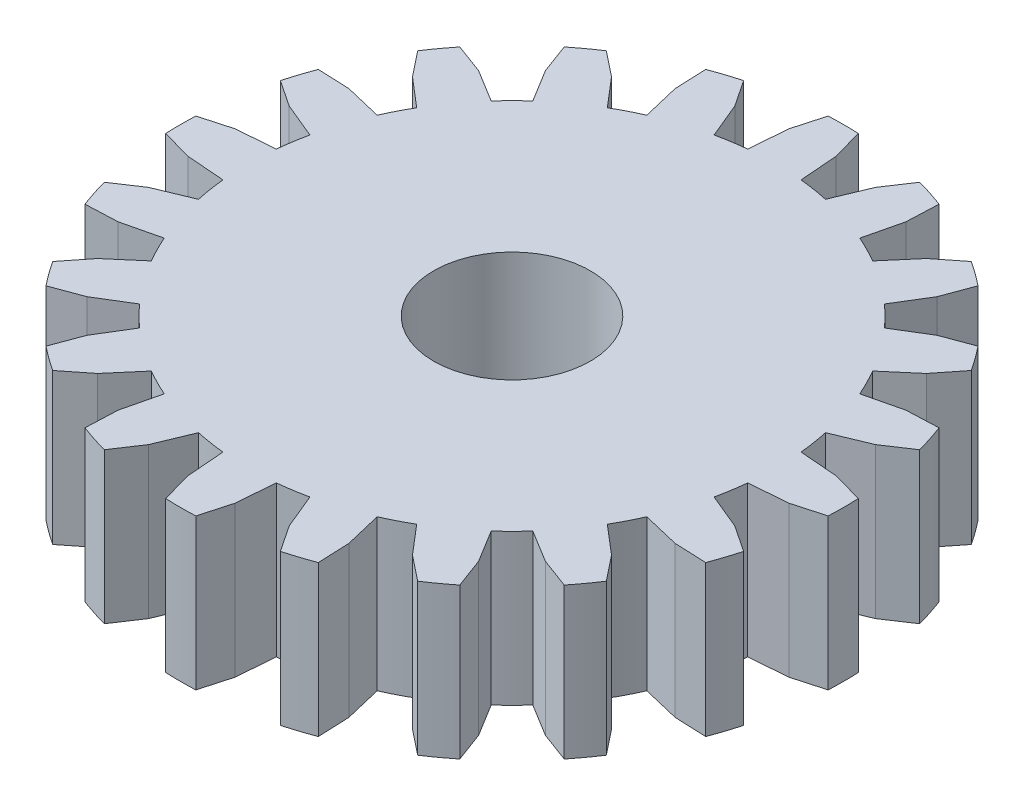
SolidWorks part; units mm, degrees
ref_plane "Front Plane" through (0, 0, 0) normal (0, 0, 1) x (1, 0, 0)
ref_plane "Top Plane" through (0, 0, 0) normal (0, 1, 0) x (1, 0, 0)
ref_plane "Right Plane" through (0, 0, 0) normal (1, 0, 0) x (0, 0, -1)
sketch "Sketch1" plane through (0, 0, 0) normal (0, 1, 0) x (1, 0, 0)
  line L0 (0, -21.5041) -> (0, 21.5041) construction
  line L1 (0.785, 9.9691) -> (0.5, 10.9886)
  line L2 (0.785, 9.9691) -> (0.885, 8.7051)
  line L3 (-0.785, 9.9691) -> (-0.885, 8.7051)
  line L4 (-0.785, 9.9691) -> (-0.5, 10.9886)
  line L5 (2.3341, 9.7238) -> (1.8483, 8.5525)
  line L6 (2.3341, 9.7238) -> (2.9201, 10.6053)
  line L7 (3.8272, 9.2386) -> (3.8712, 10.2963)
  line L8 (3.8272, 9.2386) -> (3.5317, 8.0056)
  line L9 (5.2246, 8.5266) -> (4.4008, 7.5628)
  line L10 (5.2246, 8.5266) -> (6.0544, 9.1839)
  line L11 (6.4948, 7.6038) -> (6.8635, 8.5961)
  line L12 (6.4948, 7.6038) -> (5.8327, 6.5224)
  line L13 (7.6038, 6.4948) -> (6.5224, 5.8327)
  line L14 (7.6038, 6.4948) -> (8.5961, 6.8635)
  line L15 (8.5266, 5.2246) -> (9.1839, 6.0544)
  line L16 (8.5266, 5.2246) -> (7.5628, 4.4008)
  line L17 (9.2386, 3.8272) -> (8.0056, 3.5317)
  line L18 (9.2386, 3.8272) -> (10.2963, 3.8712)
  line L19 (9.7238, 2.3341) -> (10.6053, 2.9201)
  line L20 (9.7238, 2.3341) -> (8.5525, 1.8483)
  line L21 (9.9691, 0.785) -> (8.7051, 0.885)
  line L22 (9.9691, 0.785) -> (10.9886, 0.5)
  line L23 (9.9691, -0.785) -> (10.9886, -0.5)
  line L24 (9.9691, -0.785) -> (8.7051, -0.885)
  line L25 (9.7238, -2.3341) -> (8.5525, -1.8483)
  line L26 (9.7238, -2.3341) -> (10.6053, -2.9201)
  line L27 (9.2386, -3.8272) -> (10.2963, -3.8712)
  line L28 (9.2386, -3.8272) -> (8.0056, -3.5317)
  line L29 (8.5266, -5.2246) -> (7.5628, -4.4008)
  line L30 (8.5266, -5.2246) -> (9.1839, -6.0544)
  line L31 (7.6038, -6.4948) -> (8.5961, -6.8635)
  line L32 (7.6038, -6.4948) -> (6.5224, -5.8327)
  line L33 (6.4948, -7.6038) -> (5.8327, -6.5224)
  line L34 (6.4948, -7.6038) -> (6.8635, -8.5961)
  line L35 (5.2246, -8.5266) -> (6.0544, -9.1839)
  line L36 (5.2246, -8.5266) -> (4.4008, -7.5628)
  line L37 (3.8272, -9.2386) -> (3.5317, -8.0056)
  line L38 (3.8272, -9.2386) -> (3.8712, -10.2963)
  line L39 (2.3341, -9.7238) -> (2.9201, -10.6053)
  line L40 (2.3341, -9.7238) -> (1.8483, -8.5525)
  line L41 (0.785, -9.9691) -> (0.885, -8.7051)
  line L42 (0.785, -9.9691) -> (0.5, -10.9886)
  line L43 (-0.785, -9.9691) -> (-0.5, -10.9886)
  line L44 (-0.785, -9.9691) -> (-0.885, -8.7051)
  line L45 (-2.3341, -9.7238) -> (-1.8483, -8.5525)
  line L46 (-2.3341, -9.7238) -> (-2.9201, -10.6053)
  line L47 (-3.8272, -9.2386) -> (-3.8712, -10.2963)
  line L48 (-3.8272, -9.2386) -> (-3.5317, -8.0056)
  line L49 (-5.2246, -8.5266) -> (-4.4008, -7.5628)
  line L50 (-5.2246, -8.5266) -> (-6.0544, -9.1839)
  line L51 (-6.4948, -7.6038) -> (-6.8635, -8.5961)
  line L52 (-6.4948, -7.6038) -> (-5.8327, -6.5224)
  line L53 (-7.6038, -6.4948) -> (-6.5224, -5.8327)
  line L54 (-7.6038, -6.4948) -> (-8.5961, -6.8635)
  line L55 (-8.5266, -5.2246) -> (-9.1839, -6.0544)
  line L56 (-8.5266, -5.2246) -> (-7.5628, -4.4008)
  line L57 (-9.2386, -3.8272) -> (-8.0056, -3.5317)
  line L58 (-9.2386, -3.8272) -> (-10.2963, -3.8712)
  line L59 (-9.7238, -2.3341) -> (-10.6053, -2.9201)
  line L60 (-9.7238, -2.3341) -> (-8.5525, -1.8483)
  line L61 (-9.9691, -0.785) -> (-8.7051, -0.885)
  line L62 (-9.9691, -0.785) -> (-10.9886, -0.5)
  line L63 (-9.9691, 0.785) -> (-10.9886, 0.5)
  line L64 (-9.9691, 0.785) -> (-8.7051, 0.885)
  line L65 (-9.7238, 2.3341) -> (-8.5525, 1.8483)
  line L66 (-9.7238, 2.3341) -> (-10.6053, 2.9201)
  line L67 (-9.2386, 3.8272) -> (-10.2963, 3.8712)
  line L68 (-9.2386, 3.8272) -> (-8.0056, 3.5317)
  line L69 (-8.5266, 5.2246) -> (-7.5628, 4.4008)
  line L70 (-8.5266, 5.2246) -> (-9.1839, 6.0544)
  line L71 (-7.6038, 6.4948) -> (-8.5961, 6.8635)
  line L72 (-7.6038, 6.4948) -> (-6.5224, 5.8327)
  line L73 (-6.4948, 7.6038) -> (-5.8327, 6.5224)
  line L74 (-6.4948, 7.6038) -> (-6.8635, 8.5961)
  line L75 (-5.2246, 8.5266) -> (-6.0544, 9.1839)
  line L76 (-5.2246, 8.5266) -> (-4.4008, 7.5628)
  line L77 (-3.8272, 9.2386) -> (-3.5317, 8.0056)
  line L78 (-3.8272, 9.2386) -> (-3.8712, 10.2963)
  line L79 (-2.3341, 9.7238) -> (-2.9201, 10.6053)
  line L80 (-2.3341, 9.7238) -> (-1.8483, 8.5525)
  circle A0 centre (0, 0) radius 10 construction
  circle A1 centre (0, 0) radius 8.75
  arc A2 (0.5, 10.9886) -> (-0.5, 10.9886) centre (0, 0) ccw
  arc A3 (3.8712, 10.2963) -> (2.9201, 10.6053) centre (0, 0) ccw
  arc A4 (6.8635, 8.5961) -> (6.0544, 9.1839) centre (0, 0) ccw
  arc A5 (9.1839, 6.0544) -> (8.5961, 6.8635) centre (0, 0) ccw
  arc A6 (10.6053, 2.9201) -> (10.2963, 3.8712) centre (0, 0) ccw
  arc A7 (10.9886, -0.5) -> (10.9886, 0.5) centre (0, 0) ccw
  arc A8 (10.2963, -3.8712) -> (10.6053, -2.9201) centre (0, 0) ccw
  arc A9 (8.5961, -6.8635) -> (9.1839, -6.0544) centre (0, 0) ccw
  arc A10 (6.0544, -9.1839) -> (6.8635, -8.5961) centre (0, 0) ccw
  arc A11 (2.9201, -10.6053) -> (3.8712, -10.2963) centre (0, 0) ccw
  arc A12 (-0.5, -10.9886) -> (0.5, -10.9886) centre (0, 0) ccw
  arc A13 (-3.8712, -10.2963) -> (-2.9201, -10.6053) centre (0, 0) ccw
  arc A14 (-6.8635, -8.5961) -> (-6.0544, -9.1839) centre (0, 0) ccw
  arc A15 (-9.1839, -6.0544) -> (-8.5961, -6.8635) centre (0, 0) ccw
  arc A16 (-10.6053, -2.9201) -> (-10.2963, -3.8712) centre (0, 0) ccw
  arc A17 (-10.9886, 0.5) -> (-10.9886, -0.5) centre (0, 0) ccw
  arc A18 (-10.2963, 3.8712) -> (-10.6053, 2.9201) centre (0, 0) ccw
  arc A19 (-8.5961, 6.8635) -> (-9.1839, 6.0544) centre (0, 0) ccw
  arc A20 (-6.0544, 9.1839) -> (-6.8635, 8.5961) centre (0, 0) ccw
  arc A21 (-2.9201, 10.6053) -> (-3.8712, 10.2963) centre (0, 0) ccw
  circle A23 centre (0, 0) radius 2.6
  point P5 (0.785, 9.9691)
  point P8 (0, 0)
  point P15 (-0.785, 9.9691)
  point P132 (0, 0)
  dimension "D1" = 20
  dimension "D2" = 22
  dimension "D3" = 17.5
  dimension "D7" = 20
  dimension "D8" = 5.2
  dimension "D4" = 0.785
  dimension "D5" = 0.885
  dimension "D6" = 0.5
extrude "Boss-Extrude1" add sketch "Sketch1" along normal blind 5 contours A1 | L71 A19 L70 L69 A1 L72 | L75 A20 L74 L73 A1 L76 | L7 A3 L6 L5 A1 L8 | L11 A4 L10 L9 A1 L12 | L15 A5 L14 L13 A1 L16 | L19 A6 L18 L17 A1 L20 | L23 A7 L22 L21 A1 L24 | L27 A8 L26 L25 A1 L28 | L31 A9 L30 L29 A1 L32 | L35 A10 L34 L33 A1 L36 | L39 A11 L38 L37 A1 L40 | L43 A12 L42 L41 A1 L44 | L47 A13 L46 L45 A1 L48 | L51 A14 L50 L49 A1 L52 | L55 A15 L54 L53 A1 L56 | L59 A16 L58 L57 A1 L60 | L63 A17 L62 L61 A1 L64 | L67 A18 L66 L65 A1 L68 | L1 A2 L4 L3 A1 L2 | L79 A21 L78 L77 A1 L80
sketch "Sketch2" plane through (0, 0, 0) normal (1, 0, 0) x (0, 0, -1)
  line L0 (0, -9.7626) -> (0, 9.7626) construction
  point P4 (0, 0)
